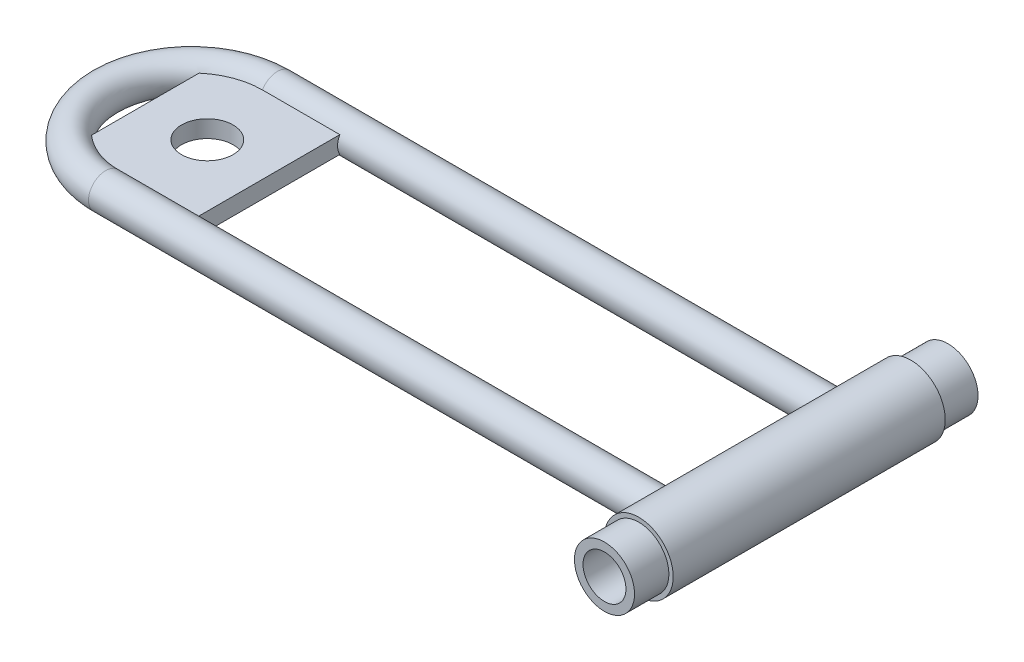
SolidWorks part; units mm, degrees
ref_plane "Front Plane" through (0, 0, 0) normal (0, 0, 1) x (1, 0, 0)
ref_plane "Top Plane" through (0, 0, 0) normal (0, 1, 0) x (1, 0, 0)
ref_plane "Right Plane" through (0, 0, 0) normal (1, 0, 0) x (0, 0, -1)
sketch "Sketch1" plane through (0, 0, 0) normal (0, 0, 1) x (1, 0, 0)
  circle A0 centre (0, 0) radius 6.35
  circle A1 centre (0, 0) radius 3.175
  dimension "D1" = 12.7
  dimension "D2" = 3.175
extrude "Boss-Extrude1" add sketch "Sketch1" along normal blind 62.992
ref_plane "Plane1" through (-3.81, 0, 0) normal (-1, 0, 0) x (0, 0, 1)
sketch "Sketch3" plane through (-3.81, 0, 0) normal (-1, 0, 0) x (0, 0, 1)
  line L0 (0, 0) -> (62.992, 0)
  line L1 (62.992, -6.35) -> (62.992, 6.35) construction
  circle A0 centre (-15.748, 0) radius 3.175
  circle A1 centre (47.244, 0) radius 3.175
  dimension "D3" = 6.35
  dimension "D4" = 6.35
  dimension "D1" = 15.748
  dimension "D2" = 15.748
sketch "Sketch4" plane through (0, 0, 0) normal (0, 1, 0) x (1, 0, 0)
  line L0 (-3.81, -15.6639) -> (-107.95, -15.6639)
  line L1 (-3.81, 0) -> (-3.81, -62.992) construction
  line L2 (-3.81, -47.0944) -> (-107.95, -47.0944)
  line L3 (-6.35, 0) -> (-6.35, -62.992) construction
  arc A0 (-107.95, -15.6639) -> (-107.95, -47.0944) centre (-107.95, -31.3792) ccw
  dimension "D1" = 101.6
  dimension "D2" = 15.7152
  dimension "D3" = 31.3792
sweep "Sweep1" add profiles "Sketch3" path "Sketch4"
ref_plane "Plane2" through (0, 0, 15.24) normal (0, 0, 1) x (1, 0, 0)
sketch "Sketch6" plane through (0, 0, 15.24) normal (0, 0, 1) x (1, 0, 0)
  line L0 (-116.5013, 0) -> (-93.6413, 0)
  line L3 (-93.6413, 0) -> (-116.5013, 0)
  line L4 (-93.6413, 0) -> (-93.6413, -1.5875)
  line L5 (-93.6413, -1.5875) -> (-116.5013, -1.5875)
  line L6 (-116.5013, 0) -> (-116.5013, -1.5875)
  line L7 (-93.6413, 0) -> (-116.5013, 0)
  line L8 (-93.6413, 0) -> (-93.6413, 1.5875)
  line L9 (-93.6413, 1.5875) -> (-116.5013, 1.5875)
  line L10 (-116.5013, 0) -> (-116.5013, 1.5875)
  circle A0 centre (0, 0) radius 3.175 construction
  point P3 (-105.0713, 0)
  dimension "D4" = 93.6413
  dimension "D1" = 22.86
  dimension "D2" = 1.5875
  dimension "D3" = 1.5875
extrude "Boss-Extrude3" add sketch "Sketch6" along normal blind 29.21 contours L0 L6 L5 L4 | L10 L0 L8 L9
sketch "Sketch7" plane through (0, 1.5875, 0) normal (0, 1, 0) x (1, 0, 0)
  line L1 (-93.6413, -44.45) -> (-93.6413, -18.2639) construction
  circle A0 centre (-105.0713, -31.3411) radius 4.7625
  dimension "D3" = 9.525
  dimension "D1" = 11.43
  dimension "D2" = 9.906
extrude "Cut-Extrude1" cut sketch "Sketch7" against normal blind 29.21
sketch "Sketch9" plane through (0, 0, 0) normal (0, 0, -1) x (-1, 0, 0)
  circle A0 centre (0, 0) radius 6.35
  circle A1 centre (0, 0) radius 3.175
  circle A2 centre (0, 0) radius 6.35 construction
  dimension "D1" = 6.35
  dimension "D2" = 12.7
ref_plane "Plane3" through (0, 0, 31.496) normal (0, 0, 1) x (1, 0, 0)
extrude "Boss-Extrude5" add sketch "Sketch9" along normal blind 6.35
mirror "Mirror1" about plane through (0, 0, 31.496) normal (0, 0, 1) of "Boss-Extrude5"
sketch "Sketch10" plane through (0, 0, 69.342) normal (0, 0, 1) x (1, 0, 0)
  circle A0 centre (0, 0) radius 5.5562
  circle A1 centre (0, 0) radius 6.35
  dimension "D1" = 11.1125
  dimension "D2" = 12.7
extrude "Cut-Extrude6" cut sketch "Sketch10" against normal blind 12.7
sketch "Sketch12" plane through (0, 0, -6.35) normal (0, 0, -1) x (-1, 0, 0)
  circle A0 centre (0, 0) radius 5.5562
  circle A1 centre (0, 0) radius 6.35
  circle A2 centre (0, 0) radius 6.35 construction
  dimension "D1" = 11.1125
  dimension "D2" = 12.7
extrude "Cut-Extrude7" cut sketch "Sketch12" against normal blind 12.7
sketch "Sketch13" plane through (0, 0, 69.342) normal (0, 0, 1) x (1, 0, 0)
  circle A0 centre (0, 0) radius 5.5563
  circle A1 centre (0, 0) radius 3.175
  circle A2 centre (0, 0) radius 3.175 construction
  dimension "D1" = 6.35
  dimension "D2" = 11.1125
extrude "Cut-Extrude8" cut sketch "Sketch13" against normal blind 6.35
sketch "Sketch14" plane through (0, 0, -6.35) normal (0, 0, -1) x (-1, 0, 0)
  circle A0 centre (0, 0) radius 5.5563
  circle A1 centre (0, 0) radius 3.175
  circle A2 centre (0, 0) radius 3.175 construction
  dimension "D1" = 6.35
  dimension "D2" = 11.1125
extrude "Cut-Extrude9" cut sketch "Sketch14" against normal blind 6.35
sketch "Sketch16" plane through (0, 0, 0) normal (0, 0, -1) x (-1, 0, 0)
  circle A0 centre (0, 0) radius 3.9688
  dimension "D1" = 7.9375
extrude "Cut-Extrude11" cut sketch "Sketch16" against normal through all
sketch "Sketch18" plane through (0, 0, 0) normal (0, 0, -1) x (-1, 0, 0)
  circle A0 centre (0, 0) radius 5.5563
  circle A1 centre (0, 0) radius 3.9688
  circle A2 centre (0, 0) radius 3.9688 construction
  dimension "D1" = 7.9375
  dimension "D2" = 11.1125
extrude "Boss-Extrude7" add sketch "Sketch18" along normal blind 0.508
